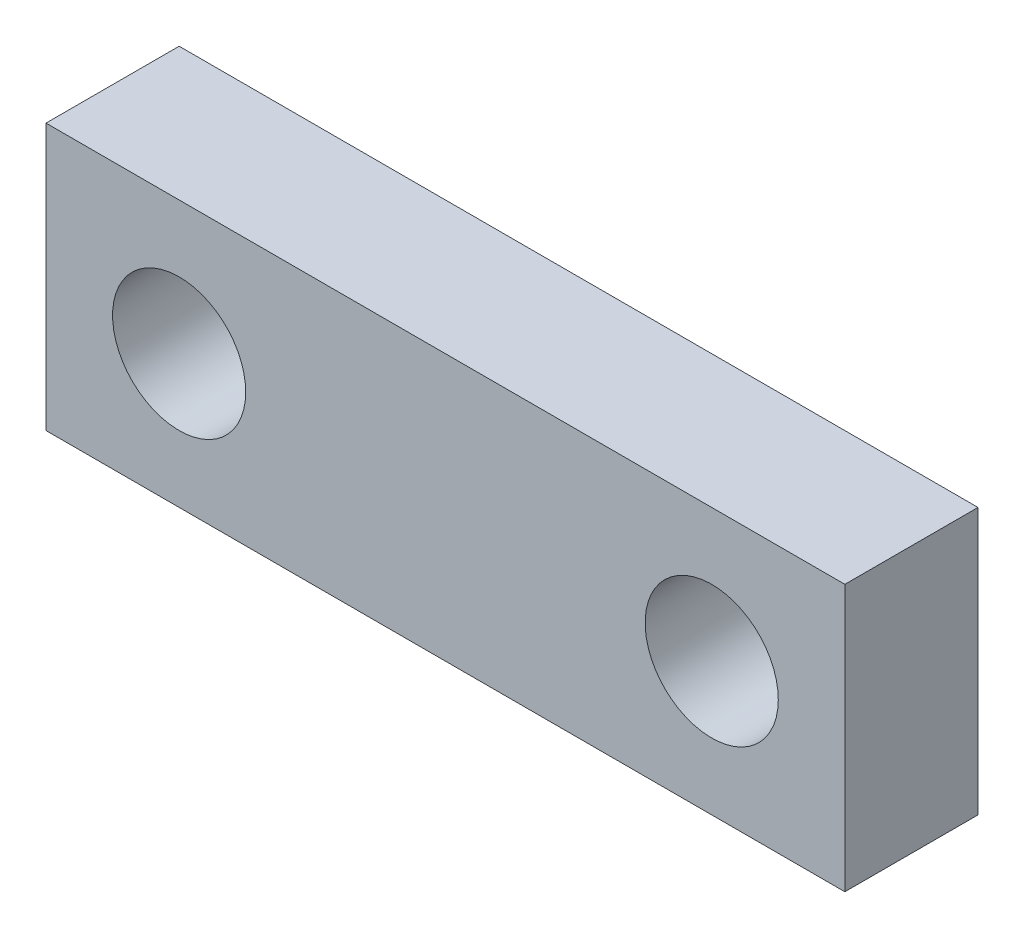
SolidWorks part; units mm, degrees
ref_plane "Front Plane" through (0, 0, 0) normal (0, 0, 1) x (1, 0, 0)
ref_plane "Top Plane" through (0, 0, 0) normal (0, 1, 0) x (1, 0, 0)
ref_plane "Right Plane" through (0, 0, 0) normal (1, 0, 0) x (0, 0, -1)
sketch "Sketch1" plane through (0, 0, 0) normal (0, 0, 1) x (1, 0, 0)
  line L1 (0, 0) -> (-30, 0)
  line L2 (0, 0) -> (0, 10)
  line L3 (0, 10) -> (-30, 10)
  line L4 (-30, 0) -> (-30, 10)
  circle A0 centre (-25, 5) radius 2.5
  circle A1 centre (-5, 5) radius 2.5
  point P9 (0, 0)
  dimension "D1" = 5
  dimension "D2" = 5
  dimension "D3" = 30
  dimension "D4" = 20
  dimension "D5" = 5
  dimension "D6" = 0
  dimension "D7" = 10
  dimension "D8" = 5
extrude "Boss-Extrude1" add sketch "Sketch1" along normal blind 5
